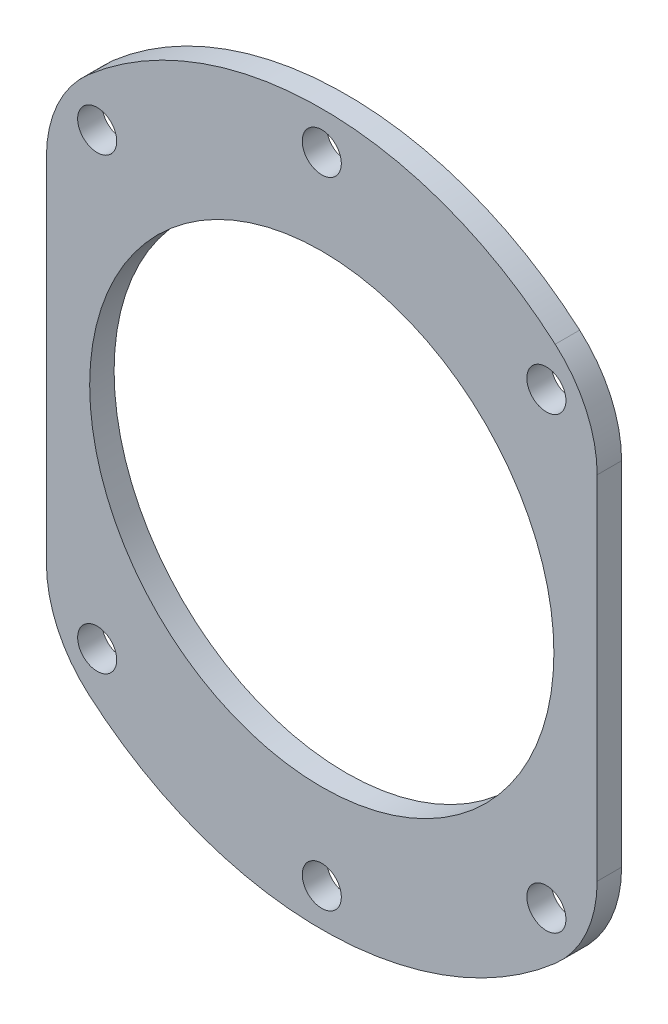
SolidWorks part; units mm, degrees
ref_plane "Front Plane" through (0, 0, 0) normal (0, 0, 1) x (1, 0, 0)
ref_plane "Top Plane" through (0, 0, 0) normal (0, 1, 0) x (1, 0, 0)
ref_plane "Right Plane" through (0, 0, 0) normal (1, 0, 0) x (0, 0, -1)
sketch "Sketch1" plane through (0, 0, 0) normal (0, 0, 1) x (1, 0, 0)
  line L2 (-81.3414, 18.4037) -> (-81.3414, -18.4037)
  line L3 (-36.2586, 18.4037) -> (-36.2586, -18.4037)
  arc A1 (-81.3414, -18.4037) -> (-36.2586, -18.4037) centre (-58.8, 0) ccw construction
  arc A11 (-81.3414, -18.4037) -> (-36.2586, -18.4037) centre (-58.8, 0) ccw
  arc A12 (-36.2586, 18.4037) -> (-81.3414, 18.4037) centre (-58.8, 0) ccw construction
  circle A13 centre (-58.8, 0) radius 19
  arc A14 (-36.2586, 18.4037) -> (-81.3414, 18.4037) centre (-58.8, 0) ccw
  point P0 (-36.2586, -9.2106)
  dimension "D1" = 38
extrude "Boss-Extrude1" add sketch "Sketch1" along normal blind 2
sketch "Sketch2" plane through (0, 0, 2) normal (0, 0, 1) x (1, 0, 0)
  circle A0 centre (-58.8, 0) radius 26 construction
  circle A1 centre (-58.8, 26) radius 1.6
  circle A2 centre (-40.4152, 18.3848) radius 1.6
  circle A4 centre (-40.4152, -18.3848) radius 1.6
  circle A5 centre (-58.8, -26) radius 1.6
  circle A6 centre (-77.1848, -18.3848) radius 1.6
  circle A8 centre (-77.1848, 18.3848) radius 1.6
  circle A9 centre (-84.8, 0) radius 1.6 [skipped]
  circle A10 centre (-32.8, 0) radius 1.6 [skipped]
  point P5 (-40.4154, -18.385)
  point P6 (-77.1679, -18.4017)
  point P22 (-58.8, 0)
  dimension "D1" = 52
  dimension "D2" = 3.2
  dimension "D3" = 8
extrude "Cut-Extrude1" cut sketch "Sketch2" against normal through all
fillet "Fillet1" radius 10 4 edges at (-81.3414, -18.4037, 1) (-81.3414, 18.4037, 1) (-36.2586, -18.4037, 1) (-36.2586, 18.4037, 1)
